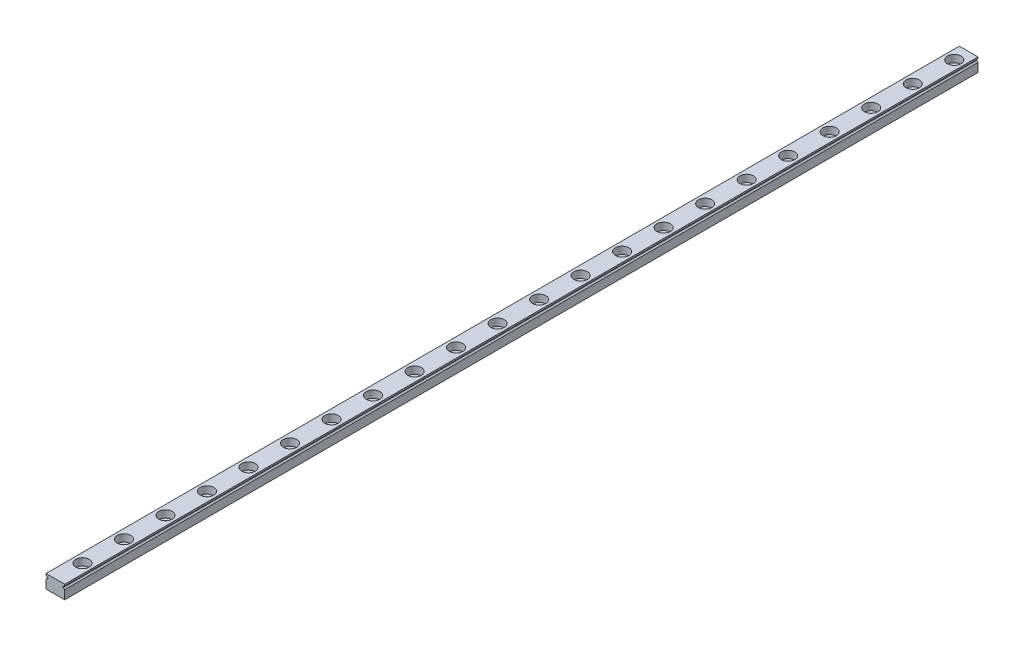
SolidWorks part; units mm, degrees
ref_plane "前视基准面" through (0, 0, 0) normal (0, 0, 1) x (1, 0, 0)
ref_plane "上视基准面" through (0, 0, 0) normal (0, 1, 0) x (1, 0, 0)
ref_plane "右视基准面" through (0, 0, 0) normal (1, 0, 0) x (0, 0, -1)
sketch "草图1" plane through (0, 0, 0) normal (0, 0, 1) x (1, 0, 0)
  line L0 (-4.5, 6.5) -> (-4.5, 0) construction
  line L1 (0, 0) -> (-9, 0)
  line L2 (0, 0) -> (0, 4.2081)
  line L3 (0, 6.5) -> (-9, 6.5)
  line L4 (-9, 0) -> (-9, 4.2081)
  line L5 (-8.0551, 4.786) -> (-8.0551, 5.1845)
  line L6 (-8.0551, 5.1845) -> (-8.3434, 5.1845)
  line L7 (-8.3434, 5.1845) -> (-9, 5.7624)
  line L8 (-8.0551, 4.786) -> (-8.3434, 4.786)
  line L9 (-8.3434, 4.786) -> (-9, 4.2081)
  line L10 (-9, 4.9853) -> (-6.6329, 4.9853) construction
  line L11 (-0.6566, 4.786) -> (0, 4.2081)
  line L12 (-0.9449, 4.786) -> (-0.6566, 4.786)
  line L13 (-0.6566, 5.1845) -> (0, 5.7624)
  line L14 (-0.9449, 5.1845) -> (-0.6566, 5.1845)
  line L15 (-0.9449, 4.786) -> (-0.9449, 5.1845)
  line L16 (0, 5.7624) -> (0, 6.5)
  line L17 (-9, 5.7624) -> (-9, 6.5)
  point P10 (-8.0551, 4.9853)
  point P22 (-0.9449, 4.9853)
  dimension "D1" = 9
  dimension "D2" = 6.5
extrude "凸台-拉伸1" add sketch "草图1" along normal blind 440
sketch "草图2" plane through (0, 6.5, 0) normal (0, 1, 0) x (1, 0, 0)
  line L0 (-4.5, 0) -> (-4.5, -10.139) construction
  line L1 (0, 0) -> (-9, 0) construction
  circle A0 centre (-4.5, -6.9424) radius 1.75
  circle A1 centre (-4.5, -26.9424) radius 1.75
  circle A2 centre (-4.5, -46.9424) radius 1.75
  circle A3 centre (-4.5, -66.9424) radius 1.75
  circle A4 centre (-4.5, -86.9424) radius 1.75
  circle A5 centre (-4.5, -106.9424) radius 1.75
  circle A6 centre (-4.5, -126.9424) radius 1.75
  circle A7 centre (-4.5, -146.9424) radius 1.75
  circle A8 centre (-4.5, -166.9424) radius 1.75
  circle A9 centre (-4.5, -186.9424) radius 1.75
  circle A10 centre (-4.5, -206.9424) radius 1.75
  circle A11 centre (-4.5, -226.9424) radius 1.75
  circle A12 centre (-4.5, -246.9424) radius 1.75
  circle A13 centre (-4.5, -266.9424) radius 1.75
  circle A14 centre (-4.5, -286.9424) radius 1.75
  circle A15 centre (-4.5, -306.9424) radius 1.75
  circle A16 centre (-4.5, -326.9424) radius 1.75
  circle A17 centre (-4.5, -346.9424) radius 1.75
  circle A18 centre (-4.5, -366.9424) radius 1.75
  circle A19 centre (-4.5, -386.9424) radius 1.75
  circle A20 centre (-4.5, -406.9424) radius 1.75
  circle A21 centre (-4.5, -426.9424) radius 1.75
  dimension "D1" = 3.5
  dimension "D2" = 22
extrude "切除-拉伸3" cut sketch "草图2" against normal blind 440
sketch "草图3" plane through (0, 6.5, 0) normal (0, 1, 0) x (1, 0, 0)
  circle A0 centre (-4.5, -6.9424) radius 3.25
  circle A1 centre (-4.5, -26.9424) radius 3.25
  circle A2 centre (-4.5, -46.9424) radius 3.25
  circle A3 centre (-4.5, -66.9424) radius 3.25
  circle A4 centre (-4.5, -86.9424) radius 3.25
  circle A5 centre (-4.5, -106.9424) radius 3.25
  circle A6 centre (-4.5, -126.9424) radius 3.25
  circle A7 centre (-4.5, -146.9424) radius 3.25
  circle A8 centre (-4.5, -166.9424) radius 3.25
  circle A9 centre (-4.5, -186.9424) radius 3.25
  circle A10 centre (-4.5, -206.9424) radius 3.25
  circle A11 centre (-4.5, -226.9424) radius 3.25
  circle A12 centre (-4.5, -246.9424) radius 3.25
  circle A13 centre (-4.5, -266.9424) radius 3.25
  circle A14 centre (-4.5, -286.9424) radius 3.25
  circle A15 centre (-4.5, -306.9424) radius 3.25
  circle A16 centre (-4.5, -326.9424) radius 3.25
  circle A17 centre (-4.5, -346.9424) radius 3.25
  circle A18 centre (-4.5, -366.9424) radius 3.25
  circle A19 centre (-4.5, -386.9424) radius 3.25
  circle A20 centre (-4.5, -406.9424) radius 3.25
  circle A21 centre (-4.5, -426.9424) radius 3.25
  circle A22 centre (-4.5, -446.9424) radius 3.25
  circle A23 centre (-4.5, -466.9424) radius 3.25
  circle A24 centre (-4.5, -486.9424) radius 3.25
  circle A25 centre (-4.5, -506.9424) radius 3.25
  circle A26 centre (-4.5, -526.9424) radius 3.25
  circle A27 centre (-4.5, -546.9424) radius 3.25
  circle A28 centre (-4.5, -566.9424) radius 3.25
  circle A29 centre (-4.5, -586.9424) radius 3.25
  circle A30 centre (-4.5, -606.9424) radius 3.25
  dimension "D1" = 6.5
  dimension "D2" = 31
extrude "切除-拉伸4" cut sketch "草图3" against normal blind 3.5
